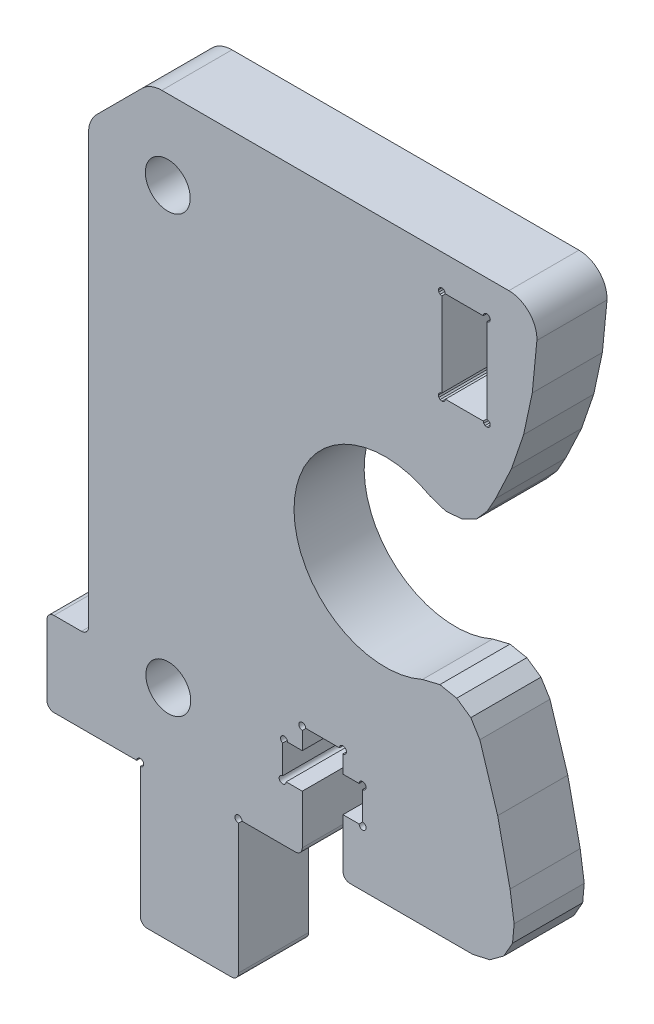
SolidWorks part; units mm, degrees
ref_plane "Plan de face" through (0, 0, 0) normal (0, 0, 1) x (1, 0, 0)
ref_plane "Plan de dessus" through (0, 0, 0) normal (0, 1, 0) x (1, 0, 0)
ref_plane "Plan de droite" through (0, 0, 0) normal (1, 0, 0) x (0, 0, -1)
ref_plane "Plan1" through (0, 0, 0) normal (0, 0, -1) x (-1, 0, 0)
sketch "Esquisse1" plane through (0, 0, 0) normal (0, 0, -1) x (-1, 0, 0)
  line L0 (-23.2017, 16.5) -> (-16.2486, 16.5) construction
  line L1 (-34.9236, 50.1856) -> (-34.5935, 46.7817)
  line L2 (-34.5935, 46.7817) -> (-33.977, 43.8958)
  line L3 (-33.977, 43.8958) -> (-33.1055, 41.3455)
  line L4 (-33.1055, 41.3455) -> (-31.9773, 38.9532)
  line L5 (-31.9773, 38.9532) -> (-31.384, 37.8844)
  line L6 (-31.384, 37.8844) -> (-30.6179, 37.0077)
  line L7 (-30.6179, 37.0077) -> (-29.5758, 36.4886)
  line L8 (-29.5758, 36.4886) -> (-28.4145, 36.4054)
  line L9 (-28.4145, 36.4054) -> (-27.309, 36.7706)
  line L10 (-23.1023, 14) -> (-16.2486, 14) construction
  line L11 (-16.8, 17.3789) -> (-16.8, 13.2369) construction
  line L12 (-22.5, 17.2001) -> (-22.5, 13.3639) construction
  line L13 (-21.1, 17.75) -> (-21.1, 18.988) construction
  line L14 (-18.2, 17.75) -> (-18.2, 18.7496) construction
  line L15 (-20.85, 18) -> (-21.9899, 18) construction
  line L16 (-18.45, 18) -> (-17.4306, 18) construction
  line L17 (-13.9, 10) -> (-12.4556, 10) construction
  line L18 (-13.65, 9.6194) -> (-13.65, 11.0115) construction
  line L24 (-26.7707, 25.1803) -> (-28.0052, 25.4813)
  line L25 (-28.0052, 25.4813) -> (-29.2063, 25.244)
  line L26 (-29.2063, 25.244) -> (-30.2127, 24.5466)
  line L27 (-30.2127, 24.5466) -> (-30.8565, 23.5051)
  line L28 (-30.8565, 23.5051) -> (-32.1273, 19.4517)
  line L29 (-32.1273, 19.4517) -> (-33.011, 15.3627)
  line L30 (-33.011, 15.3627) -> (-33.3011, 13.3639)
  line L31 (-33.3011, 13.3639) -> (-33.1879, 12.1092)
  line L32 (-33.1879, 12.1092) -> (-32.5696, 11.0115)
  line L33 (-32.5696, 11.0115) -> (-31.555, 10.2645)
  line L34 (-31.555, 10.2645) -> (-30.3233, 10)
  line L35 (-30.3233, 10) -> (-21.6, 10)
  line L39 (-21.1, 10.5) -> (-21.1, 14)
  line L40 (-21.1, 14) -> (-22.25, 14)
  line L50 (-22.5, 14.25) -> (-22.5, 16.25)
  line L60 (-22.25, 16.5) -> (-21.1, 16.5)
  line L61 (-21.1, 16.5) -> (-21.1, 17.75)
  line L71 (-20.85, 18) -> (-18.45, 18)
  line L81 (-18.2, 17.75) -> (-18.2, 16.5)
  line L82 (-18.2, 16.5) -> (-17.15, 16.5)
  line L92 (-16.8, 16.2709) -> (-16.8, 14.25)
  line L102 (-17.05, 14) -> (-18.2, 14)
  line L103 (-18.2, 14) -> (-18.2, 10.5)
  line L107 (-17.7, 10) -> (-13.9, 10)
  line L117 (-13.65, 9.75) -> (-13.65, 0.5)
  line L121 (-13.15, 0) -> (-7.15, 0)
  line L125 (-6.65, 0.5) -> (-6.65, 9.75)
  line L126 (-6.65, 9.75) -> (-6.775, 9.7835)
  line L127 (-6.775, 9.7835) -> (-6.8665, 9.875)
  line L128 (-6.8665, 9.875) -> (-6.9, 10)
  line L129 (-6.9, 10) -> (-6.8665, 10.125)
  line L130 (-6.8665, 10.125) -> (-6.775, 10.2165)
  line L131 (-6.775, 10.2165) -> (-6.65, 10.25)
  line L132 (-6.65, 10.25) -> (-6.525, 10.2165)
  line L133 (-6.525, 10.2165) -> (-6.4335, 10.125)
  line L134 (-6.4335, 10.125) -> (-6.4, 10)
  line L135 (-6.4, 10) -> (-0.5, 10)
  line L139 (0, 10.5) -> (0, 15.5)
  line L143 (-0.5, 16) -> (-2.4614, 16)
  line L147 (-2.9614, 16.5) -> (-2.9614, 47.033)
  line L150 (-3.5472, 48.4473) -> (-6.7757, 51.6757)
  line L153 (-8.1899, 52.2615) -> (-32.925, 52.2615)
  line L157 (-31.6, 43.3) -> (-31.5665, 43.425)
  line L158 (-31.5665, 43.425) -> (-31.475, 43.5165)
  line L159 (-31.475, 43.5165) -> (-31.35, 43.55)
  line L160 (-31.35, 43.55) -> (-31.35, 49.55)
  line L161 (-31.35, 49.55) -> (-31.475, 49.5835)
  line L162 (-31.475, 49.5835) -> (-31.5665, 49.675)
  line L163 (-31.5665, 49.675) -> (-31.6, 49.8)
  line L164 (-31.6, 49.8) -> (-31.5665, 49.925)
  line L165 (-31.5665, 49.925) -> (-31.475, 50.0165)
  line L166 (-31.475, 50.0165) -> (-31.35, 50.05)
  line L167 (-31.35, 50.05) -> (-31.225, 50.0165)
  line L168 (-31.225, 50.0165) -> (-31.1335, 49.925)
  line L169 (-31.1335, 49.925) -> (-31.1, 49.8)
  line L170 (-31.1, 49.8) -> (-28.4, 49.8)
  line L171 (-28.4, 49.8) -> (-28.3665, 49.925)
  line L172 (-28.3665, 49.925) -> (-28.275, 50.0165)
  line L173 (-28.275, 50.0165) -> (-28.15, 50.05)
  line L174 (-28.15, 50.05) -> (-28.025, 50.0165)
  line L175 (-28.025, 50.0165) -> (-27.9335, 49.925)
  line L176 (-27.9335, 49.925) -> (-27.9, 49.8)
  line L177 (-27.9, 49.8) -> (-27.9335, 49.675)
  line L178 (-27.9335, 49.675) -> (-28.025, 49.5835)
  line L179 (-28.025, 49.5835) -> (-28.15, 49.55)
  line L180 (-28.15, 49.55) -> (-28.15, 43.55)
  line L181 (-28.15, 43.55) -> (-28.025, 43.5165)
  line L182 (-28.025, 43.5165) -> (-27.9335, 43.425)
  line L183 (-27.9335, 43.425) -> (-27.9, 43.3)
  line L184 (-27.9, 43.3) -> (-27.9335, 43.175)
  line L185 (-27.9335, 43.175) -> (-28.025, 43.0835)
  line L186 (-28.025, 43.0835) -> (-28.15, 43.05)
  line L187 (-28.15, 43.05) -> (-28.275, 43.0835)
  line L188 (-28.275, 43.0835) -> (-28.3665, 43.175)
  line L189 (-28.3665, 43.175) -> (-28.4, 43.3)
  line L190 (-28.4, 43.3) -> (-31.1, 43.3)
  line L191 (-31.1, 43.3) -> (-31.1335, 43.175)
  line L192 (-31.1335, 43.175) -> (-31.225, 43.0835)
  line L193 (-31.225, 43.0835) -> (-31.35, 43.05)
  line L194 (-31.35, 43.05) -> (-31.475, 43.0835)
  line L195 (-31.475, 43.0835) -> (-31.5665, 43.175)
  line L196 (-31.5665, 43.175) -> (-31.6, 43.3)
  circle A0 centre (-8.6115, 46.6115) radius 1.6
  circle A1 centre (-8.65, 15.6115) radius 1.6
  arc A2 (-26.7707, 25.1803) -> (-27.309, 36.7706) centre (-24.1115, 31.1115) ccw
  arc A3 (-13.15, 0) -> (-13.65, 0.5) centre (-13.15, 0.5) cw
  arc A4 (-6.65, 0.5) -> (-7.15, 0) centre (-7.15, 0.5) cw
  arc A5 (-0.5, 10) -> (0, 10.5) centre (-0.5, 10.5) ccw
  arc A6 (0, 15.5) -> (-0.5, 16) centre (-0.5, 15.5) ccw
  arc A7 (-2.4614, 16) -> (-2.9614, 16.5) centre (-2.4614, 16.5) cw
  arc A8 (-2.9614, 47.033) -> (-3.5472, 48.4473) centre (-4.9615, 47.033) ccw
  arc A9 (-6.7757, 51.6757) -> (-8.1899, 52.2615) centre (-8.1899, 50.2614) ccw
  arc A10 (-32.925, 52.2615) -> (-34.9236, 50.1856) centre (-32.925, 50.2615) ccw
  arc A11 (-17.7, 10) -> (-18.2, 10.5) centre (-17.7, 10.5) cw
  arc A12 (-21.1, 10.5) -> (-21.6, 10) centre (-21.6, 10.5) cw
  arc A13 (-20.85, 18) -> (-21.1, 17.75) centre (-21.1, 18) ccw
  arc A14 (-18.2, 17.75) -> (-18.45, 18) centre (-18.2, 18) ccw
  arc A15 (-16.8, 16.2709) -> (-17.15, 16.5) centre (-16.9, 16.5) ccw
  arc A16 (-17.05, 14) -> (-16.8, 14.25) centre (-16.8, 14) ccw
  arc A17 (-22.25, 16.5) -> (-22.5, 16.25) centre (-22.5, 16.5) ccw
  arc A18 (-22.5, 14.25) -> (-22.25, 14) centre (-22.5, 14) ccw
  arc A19 (-13.65, 9.75) -> (-13.9, 10) centre (-13.65, 10) ccw
  dimension "D1" = 3.2
  dimension "D2" = 46.6115
  dimension "D4" = 3.2
  dimension "D5" = 31
  dimension "D6" = 8.65
  dimension "D9" = 6.5
  dimension "D10" = 15.5
  dimension "D11" = 15.5
  dimension "D12" = 0.25
  dimension "D13" = 0.25
  dimension "D14" = 0.25
  dimension "D15" = 0.25
  dimension "D16" = 0.25
  dimension "D17" = 0.25
  dimension "D24" = 0.25
  dimension "D3" = 8.6115
  dimension "D7" = 6
  dimension "D8" = 10
  dimension "D18" = 2.5
  dimension "D19" = 2.9
  dimension "D20" = 1.5
  dimension "D21" = 4
  dimension "D22" = 1.4
  dimension "D23" = 1.4
extrude "Boss.-Extru.1" add sketch "Esquisse1" against normal blind 5
